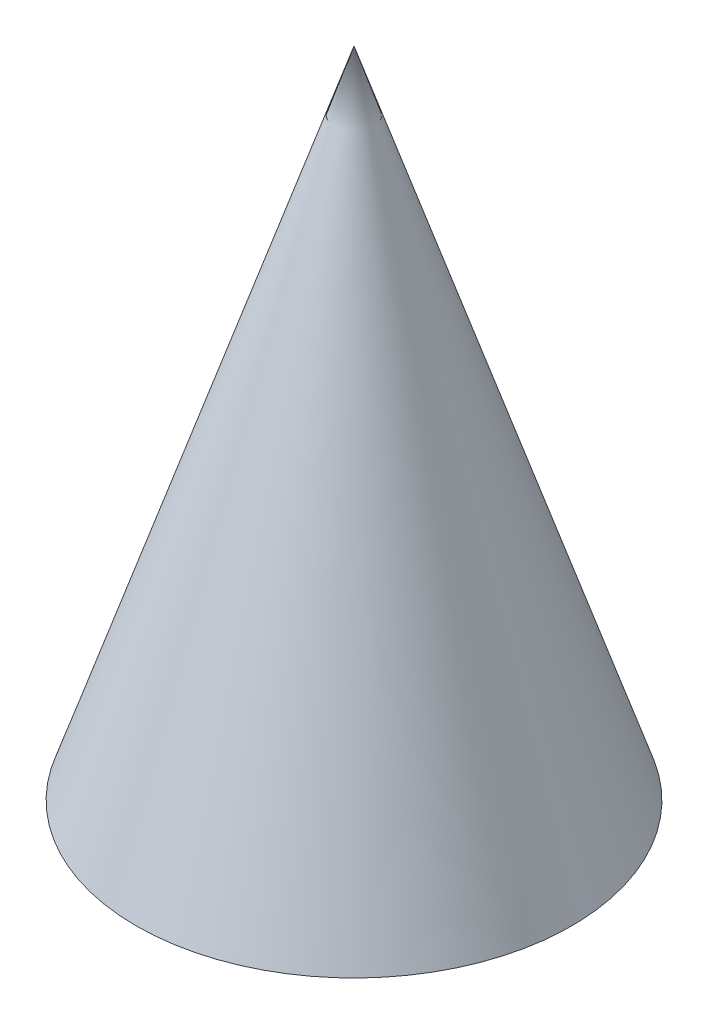
SolidWorks part; units mm, degrees
ref_plane "Front" through (0, 0, 0) normal (0, 0, 1) x (1, 0, 0)
ref_plane "Top" through (0, 0, 0) normal (0, 1, 0) x (1, 0, 0)
ref_plane "Right" through (0, 0, 0) normal (1, 0, 0) x (0, 0, -1)
sketch "Sketch1" plane through (0, 0, 0) normal (0, 0, 1) x (1, 0, 0)
  line L0 (0, 0) -> (0, 76.2)
  line L1 (0, 76.2) -> (25.4, 0)
  line L2 (25.4, 0) -> (0, 0)
  dimension "D1" = 25.4
  dimension "D2" = 76.2
revolve "Revolve1" add sketch "Sketch1" angle 360 about L0
